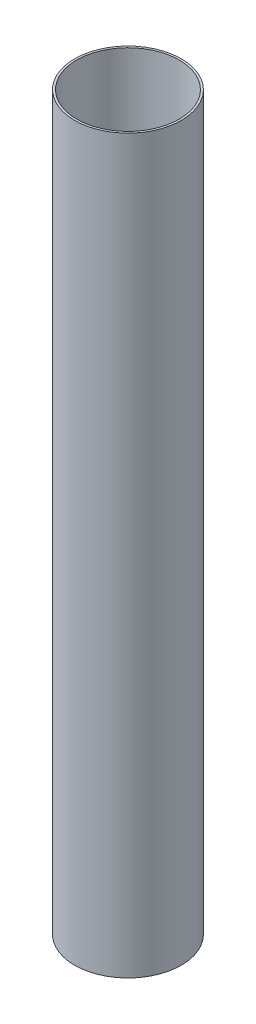
SolidWorks part; units mm, degrees
ref_plane "Front Plane" through (0, 0, 0) normal (0, 0, 1) x (1, 0, 0)
ref_plane "Top Plane" through (0, 0, 0) normal (0, 1, 0) x (1, 0, 0)
ref_plane "Right Plane" through (0, 0, 0) normal (1, 0, 0) x (0, 0, -1)
sketch "Sketch1" plane through (0, 0, 0) normal (0, 1, 0) x (1, 0, 0)
  circle A0 centre (0, 0) radius 49.2
  circle A1 centre (0, 0) radius 51.2
  dimension "D1" = 98.4
  dimension "D2" = 2
extrude "Boss-Extrude1" add sketch "Sketch1" along normal blind 702
